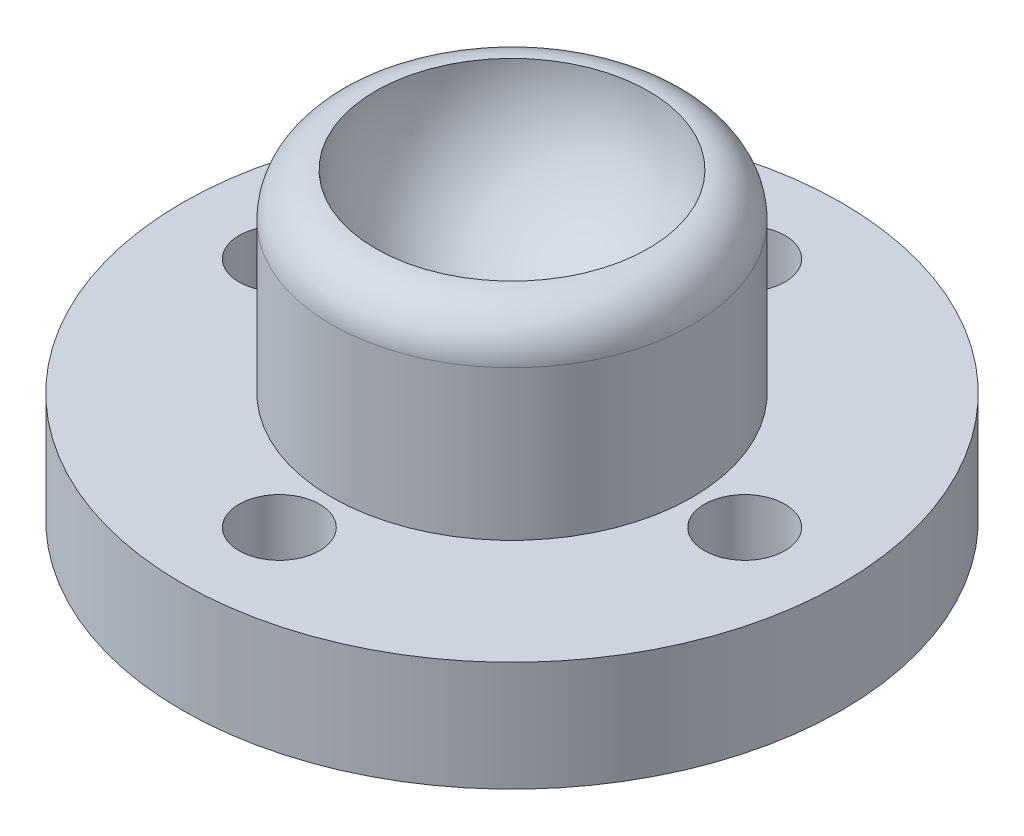
SolidWorks part; units mm, degrees
ref_plane "Front Plane" through (0, 0, 0) normal (0, 0, 1) x (1, 0, 0)
ref_plane "Top Plane" through (0, 0, 0) normal (0, 1, 0) x (1, 0, 0)
ref_plane "Right Plane" through (0, 0, 0) normal (1, 0, 0) x (0, 0, -1)
sketch "Sketch2" plane through (0, 0, 0) normal (0, 1, 0) x (1, 0, 0)
  circle A0 centre (0, 0) radius 19.05
  circle A1 centre (0, 0) radius 6.6888
  circle A2 centre (0, 0) radius 13.4442 construction
  circle A3 centre (0, 13.4442) radius 2.3288
  circle A4 centre (13.4442, 0) radius 2.3288
  circle A5 centre (0, -13.4442) radius 2.3288
  circle A6 centre (-13.4442, 0) radius 2.3288
  point P16 (0, 0)
  dimension "D1" = 38.1
  dimension "D2" = 4
extrude "Boss-Extrude1" add sketch "Sketch2" along normal blind 6.35
sketch "Sketch3" plane through (0, 6.35, 0) normal (0, 1, 0) x (1, 0, 0)
  circle A0 centre (0, 0) radius 10.4245
extrude "Boss-Extrude2" add sketch "Sketch3" along normal blind 11.176
fillet "Fillet1" radius 2.54 1 edges at (0, 17.526, 10.4245)
sketch "Sketch5" plane through (0, 17.526, 0) normal (0, 1, 0) x (1, 0, 0)
  line L0 (0, 14.2957) -> (0, -13.5447) construction
  line L1 (0, 7.8845) -> (0, -7.8845)
  arc A0 (0, -7.8845) -> (0, 7.8845) centre (0, 0) ccw
  dimension "D1" = 7.8845
revolve "Revolve1" add sketch "Sketch5" angle 360 about L0
combine bodies "Combine1" operation type subtract main body 102 bodies to subtract 103
